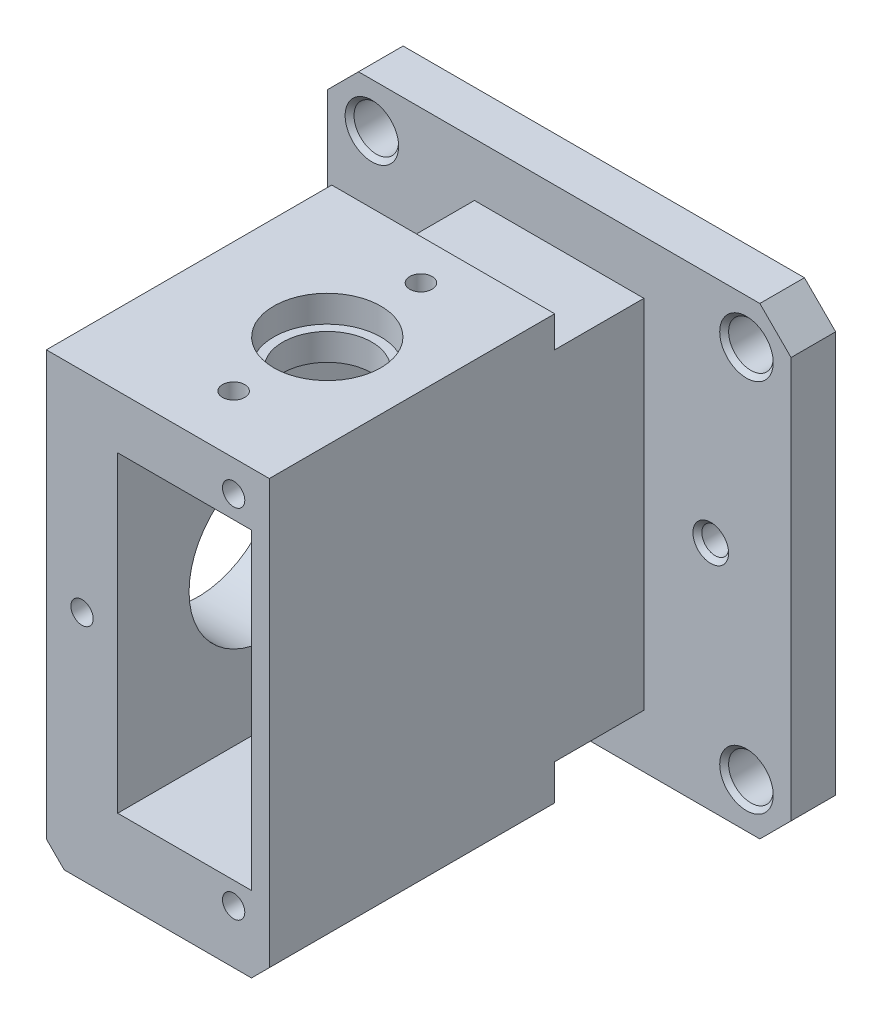
SolidWorks part; units mm, degrees
material "Сталь 10кп ГОСТ 535-88"
ref_plane "Спереди" through (0, 0, 0) normal (0, 0, 1) x (1, 0, 0)
ref_plane "Сверху" through (0, 0, 0) normal (0, 1, 0) x (1, 0, 0)
ref_plane "Справа" through (0, 0, 0) normal (1, 0, 0) x (0, 0, -1)
sketch "Эскиз1" plane through (0, 0, 0) normal (0, 0, 1) x (1, 0, 0)
  line L1 (-26, -26) -> (26, -26)
  line L2 (-26, -26) -> (-26, 26)
  line L3 (-26, 26) -> (26, 26)
  line L4 (26, -26) -> (26, 26)
  line L5 (-26, -26) -> (26, 26) construction
  line L6 (-26, 26) -> (26, -26) construction
  point P0 (0, 0)
  dimension "D1" = 52
extrude "Бобышка-Вытянуть1" add sketch "Эскиз1" along normal blind 5
sketch "Эскиз2" plane through (0, 0, 5) normal (0, 0, 1) x (1, 0, 0)
  line L1 (-21, -21) -> (21, -21)
  line L2 (-21, -21) -> (-21, 21)
  line L3 (-21, 21) -> (21, 21)
  line L4 (21, -21) -> (21, 21)
  line L5 (-21, -21) -> (21, 21) construction
  line L6 (-21, 21) -> (21, -21) construction
  circle A0 centre (21, 21) radius 2.5
  circle A1 centre (21, -21) radius 2.5
  circle A2 centre (-21, -21) radius 2.5
  circle A3 centre (-21, 21) radius 2.5
  point P0 (0, 0)
  dimension "D2" = 5
  dimension "D1" = 42
extrude "Вырез-Вытянуть1" cut sketch "Эскиз2" against normal through all contours L3 A3 L2 | L4 A0 L3 | L3 A0 L4 | L2 A3 L3 | L2 A2 L1 | L1 A2 L2 | L1 A1 L4 | L4 A1 L1
chamfer "Фаска1" distance 3.5 angle 45 4 edges at (-26, 26, 2.5) (26, 26, 2.5) (26, -26, 2.5) (-26, -26, 2.5)
chamfer "Фаска2" distance 0.5 angle 45 4 edges at (23.5, -21, 5) (23.5, 21, 5) (-18.5, 21, 5) (-18.5, -21, 5)
sketch "Эскиз3" plane through (0, 0, 5) normal (0, 0, 1) x (1, 0, 0)
  line L0 (-26, 0) -> (26, 0) construction
  line L1 (-26, 22.5) -> (-26, -22.5) construction
  line L2 (26, -22.5) -> (26, 22.5) construction
  line L4 (9.5, -20) -> (-9.5, -20)
  line L5 (9.5, -20) -> (9.5, 20)
  line L6 (9.5, 20) -> (-9.5, 20)
  line L7 (-9.5, -20) -> (-9.5, 20)
  line L8 (9.5, -20) -> (-9.5, 20) construction
  line L9 (9.5, 20) -> (-9.5, -20) construction
  point P6 (0, 0)
  dimension "D1" = 19
  dimension "D2" = 40
extrude "Бобышка-Вытянуть2" add sketch "Эскиз3" along normal blind 42
sketch "Эскиз6" plane through (0, 0, 47) normal (0, 0, 1) x (1, 0, 0)
  line L1 (-7.5, -17.5) -> (7.5, -17.5)
  line L2 (-7.5, -17.5) -> (-7.5, 17.5)
  line L3 (-7.5, 17.5) -> (7.5, 17.5)
  line L4 (7.5, -17.5) -> (7.5, 17.5)
  line L5 (-7.5, -17.5) -> (7.5, 17.5) construction
  line L6 (-7.5, 17.5) -> (7.5, -17.5) construction
  point P0 (0, 0)
  dimension "D1" = 15
  dimension "D2" = 35
sketch "Эскиз4" plane through (0, 0, 47) normal (0, 0, 1) x (1, 0, 0)
  line L0 (22.5, 26) -> (-22.5, 26) construction
  line L1 (-15.5, -26) -> (9.5, -26)
  line L2 (-15.5, -26) -> (-15.5, 26)
  line L3 (-15.5, 26) -> (9.5, 26)
  line L4 (9.5, -26) -> (9.5, 26)
  line L5 (-15.5, -26) -> (9.5, 26) construction
  line L6 (-15.5, 26) -> (9.5, -26) construction
  line L7 (9.5, -20) -> (9.5, 20) construction
  point P0 (-3, 0)
  dimension "D1" = 25
extrude "Бобышка-Вытянуть3" add sketch "Эскиз4" against normal blind 32
extrude "Вырез-Вытянуть2" cut sketch "Эскиз6" against normal through all
sketch "Эскиз7" plane through (-15.5, 0, 0) normal (-1, 0, 0) x (0, 0, 1)
  line L0 (15, 26) -> (15, -26) construction
  circle A0 centre (30, 0) radius 9
  dimension "D1" = 18
  dimension "D2" = 15
extrude "Вырез-Вытянуть3" cut sketch "Эскиз7" against normal up to next
sketch "Эскиз8" plane through (-15.5, 0, 0) normal (-1, 0, 0) x (0, 0, 1)
  line L1 (21, 11) -> (39, 11) construction
  line L2 (21, 11) -> (21, -11) construction
  line L3 (21, -11) -> (39, -11) construction
  line L4 (39, 11) -> (39, -11) construction
  line L5 (21, 11) -> (39, -11) construction
  line L6 (21, -11) -> (39, 11) construction
  point P0 (30, 0)
  dimension "D1" = 18
  dimension "D2" = 22
hole_wizard "Отверстие обработанное метчиком M3x0.51" positions "Трехмерный эскиз1" profile "Эскиз9" tap size "M3x0.5" standard "Ansi Metric"
sketch3d "Трехмерный эскиз1"
  point P0 (-15.5, 11, 39)
  point P3 (-15.5, -11, 39)
  point P6 (-15.5, -11, 21)
  point P9 (-15.5, 11, 21)
sketch "Эскиз9" plane through (-15.5, 11, 39) normal (0, 1, 0) x (0, 0, 1)
  line L0 (0, 0) -> (0, 6.2511)
  line L1 (0, 6.2511) -> (1.25, 5.5)
  line L2 (1.25, 5.5) -> (1.25, 0)
  line L5 (1.25, 0) -> (0, 0)
  line L10 (0, 6.2511) -> (-1.25, 5.5) construction
  line L11 (0, -6.35) -> (0, 107.95) construction
  dimension "Диаметр сверла" = 2.5
  dimension "Глубина сверла" = 5.5
  dimension "Угол заточки сверла" = 118
cosmetic thread "Отверстие резьбы1" parameters "D1"=4, "D2"=3
cosmetic thread "Отверстие резьбы2" parameters "D1"=4, "D2"=3
cosmetic thread "Отверстие резьбы3" parameters "D1"=4, "D2"=3
cosmetic thread "Отверстие резьбы4" parameters "D1"=4, "D2"=3
chamfer "Фаска3" distance 2 angle 45 4 edges at (9.5, -26, 31) (9.5, 26, 31) (-15.5, 26, 31) (-15.5, -26, 31)
sketch "Эскиз11" plane through (0, 0, 47) normal (0, 0, 1) x (1, 0, 0)
  point P0 (5.5, 20)
  point P1 (-11.5, 0)
  point P3 (5.5, -20)
hole_wizard "Отверстие обработанное метчиком M3x0.52" positions "Трехмерный эскиз3" profile "Эскиз12" tap size "M3x0.5" standard "Ansi Metric"
sketch3d "Трехмерный эскиз3"
  point P0 (5.5, 20, 47)
  point P3 (-11.5, 0, 47)
  point P6 (5.5, -20, 47)
sketch "Эскиз12" plane through (5.5, 20, 47) normal (1, 0, 0) x (0, -1, 0)
  line L0 (0, 0) -> (0, 6.2511)
  line L1 (0, 6.2511) -> (1.25, 5.5)
  line L2 (1.25, 5.5) -> (1.25, 0)
  line L5 (1.25, 0) -> (0, 0)
  line L10 (0, 6.2511) -> (-1.25, 5.5) construction
  line L11 (0, -6.35) -> (0, 107.95) construction
  dimension "Диаметр сверла" = 2.5
  dimension "Глубина сверла" = 5.5
  dimension "Угол заточки сверла" = 118
cosmetic thread "Отверстие резьбы5" parameters "D1"=4, "D2"=3
cosmetic thread "Отверстие резьбы6" parameters "D1"=4, "D2"=3
cosmetic thread "Отверстие резьбы7" parameters "D1"=4, "D2"=3
sketch "Эскиз13" plane through (0, -26, 0) normal (0, -1, 0) x (-1, 0, 0)
  line L0 (26, 0) -> (26, -5) construction
  line L1 (22.5, 0) -> (-22.5, 0) construction
  circle A0 centre (1, -30) radius 3.1
  dimension "D3" = 6.2
  dimension "D1" = 25
  dimension "D2" = 30
extrude "Вырез-Вытянуть4" cut sketch "Эскиз13" against normal blind 7
sketch "Эскиз14" plane through (0, -19, 0) normal (0, -1, 0) x (1, 0, 0)
  circle A0 centre (-1, 30) radius 2.05
  dimension "D1" = 4.1
extrude "Вырез-Вытянуть5" cut sketch "Эскиз14" against normal up to next
chamfer "Фаска4" distance 1 angle 45 1 edges at (-1, -26, 26.9)
sketch "Эскиз15" plane through (0, 26, 0) normal (0, 1, 0) x (1, 0, 0)
  line L1 (-15.5, -47) -> (9.5, -47)
  line L2 (-15.5, -47) -> (-15.5, -15)
  line L3 (-15.5, -15) -> (9.5, -15)
  line L4 (9.5, -47) -> (9.5, -15)
extrude "Вырез-Вытянуть6" cut sketch "Эскиз15" against normal blind 2.5
sketch "Эскиз16" plane through (0, 23.5, 0) normal (0, 1, 0) x (1, 0, 0)
  circle A0 centre (-1, -30) radius 6
  dimension "D1" = 12
extrude "Вырез-Вытянуть7" cut sketch "Эскиз16" against normal blind 3
sketch "Эскиз17" plane through (0, 20.5, 0) normal (0, 1, 0) x (1, 0, 0)
  circle A0 centre (-1, -30) radius 5
  dimension "D1" = 10
extrude "Вырез-Вытянуть8" cut sketch "Эскиз17" against normal up to next
sketch "Эскиз18" plane through (0, 23.5, 0) normal (0, 1, 0) x (1, 0, 0)
  line L0 (-1, -30) -> (-1, -47) construction
  line L1 (-15.5, -47) -> (9.5, -47) construction
  line L2 (-1, -30) -> (-1, -15) construction
  line L3 (9.5, -15) -> (-15.5, -15) construction
  point P5 (-1, -40.5)
  point P9 (-1, -19.5)
  dimension "D1" = 10.5
  dimension "D2" = 10.5
hole_wizard "Отверстие обработанное метчиком M3x0.53" positions "Трехмерный эскиз4" profile "Эскиз19" tap size "M3x0.5" standard "Ansi Metric"
sketch3d "Трехмерный эскиз4"
  point P0 (-1, 23.5, 40.5)
  point P3 (-1, 23.5, 19.5)
sketch "Эскиз19" plane through (-1, 23.5, 40.5) normal (1, 0, 0) x (0, 0, 1)
  line L0 (0, 0) -> (0, 5.2511)
  line L1 (0, 5.2511) -> (1.25, 4.5)
  line L2 (1.25, 4.5) -> (1.25, 0)
  line L5 (1.25, 0) -> (0, 0)
  line L10 (0, 5.2511) -> (-1.25, 4.5) construction
  line L11 (0, -6.35) -> (0, 107.95) construction
  dimension "Диаметр сверла" = 2.5
  dimension "Глубина сверла" = 4.5
  dimension "Угол заточки сверла" = 118
cosmetic thread "Отверстие резьбы8" parameters "D1"=3.5, "D2"=3
cosmetic thread "Отверстие резьбы9" parameters "D1"=3.5, "D2"=3
sketch "Эскиз20" plane through (0, 0, 0) normal (0, 0, -1) x (-1, 0, 0)
  line L0 (-26, 0) -> (26, 0) construction
  line L1 (-26, -22.5) -> (-26, 22.5) construction
  line L2 (26, 22.5) -> (26, -22.5) construction
  circle A0 centre (-17, 0) radius 1.5
  circle A1 centre (17, 0) radius 1.5
  dimension "D1" = 3
  dimension "D2" = 9
  dimension "D3" = 9
extrude "Вырез-Вытянуть9" cut sketch "Эскиз20" against normal up to next
chamfer "Фаска5" distance 0.5 angle 45 2 edges at (15.5, 0, 5) (-18.5, 0, 5)
